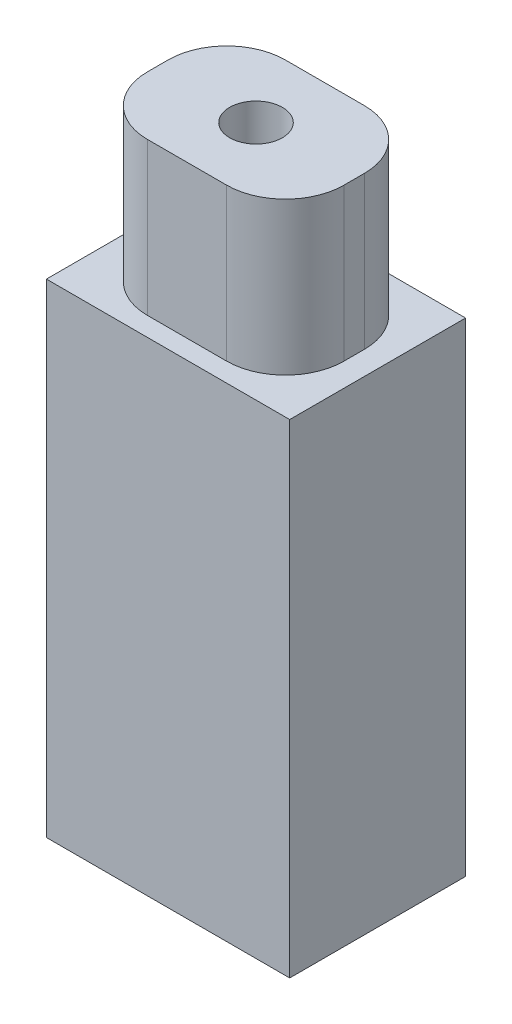
SolidWorks part; units mm, degrees
ref_plane "Front Plane" through (0, 0, 0) normal (0, 0, 1) x (1, 0, 0)
ref_plane "Top Plane" through (0, 0, 0) normal (0, 1, 0) x (1, 0, 0)
ref_plane "Right Plane" through (0, 0, 0) normal (1, 0, 0) x (0, 0, -1)
sketch "Sketch1" plane through (0, 0, 0) normal (0, 0, 1) x (1, 0, 0)
  line L1 (10.541, -20.955) -> (-10.541, -20.955)
  line L2 (10.541, -20.955) -> (10.541, 20.955)
  line L3 (10.541, 20.955) -> (-10.541, 20.955)
  line L4 (-10.541, -20.955) -> (-10.541, 20.955)
  line L5 (10.541, -20.955) -> (-10.541, 20.955) construction
  line L6 (10.541, 20.955) -> (-10.541, -20.955) construction
  point P0 (0, 0)
  dimension "D1" = 41.91
  dimension "D2" = 21.082
extrude "Boss-Extrude1" add sketch "Sketch1" along normal blind 15.24
sketch "Sketch2" plane through (0, 20.955, 0) normal (0, 1, 0) x (1, 0, 0)
  line L0 (-10.541, -7.62) -> (-0.821, -7.62) construction
  line L1 (3.429, -13.589) -> (-3.429, -13.589)
  line L2 (8.509, -8.509) -> (8.509, -6.731)
  line L3 (3.429, -1.651) -> (-3.429, -1.651)
  line L4 (-8.509, -8.509) -> (-8.509, -6.731)
  line L5 (8.509, -13.589) -> (-8.509, -1.651) construction
  line L6 (8.509, -1.651) -> (-8.509, -13.589) construction
  line L7 (-10.541, -15.24) -> (-10.541, 0) construction
  arc A0 (3.429, -13.589) -> (8.509, -8.509) centre (3.429, -8.509) ccw
  arc A1 (-8.509, -6.731) -> (-3.429, -1.651) centre (-3.429, -6.731) cw
  arc A2 (-3.429, -13.589) -> (-8.509, -8.509) centre (-3.429, -8.509) cw
  arc A3 (8.509, -6.731) -> (3.429, -1.651) centre (3.429, -6.731) ccw
  point P0 (0, -7.62)
  dimension "D3" = 5.08
  dimension "D4" = 5.08
  dimension "D1" = 17.018
  dimension "D2" = 11.938
extrude "Boss-Extrude2" add sketch "Sketch2" along normal blind 13.208
sketch "Sketch3" plane through (0, 34.163, 0) normal (0, 1, 0) x (1, 0, 0)
  line L0 (-8.509, -7.62) -> (-2.7685, -7.62) construction
  line L1 (-8.509, -6.731) -> (-8.509, -8.509) construction
  circle A0 centre (0, -7.62) radius 2.286
  dimension "D1" = 4.572
extrude "Cut-Extrude1" cut sketch "Sketch3" against normal blind 10.16
